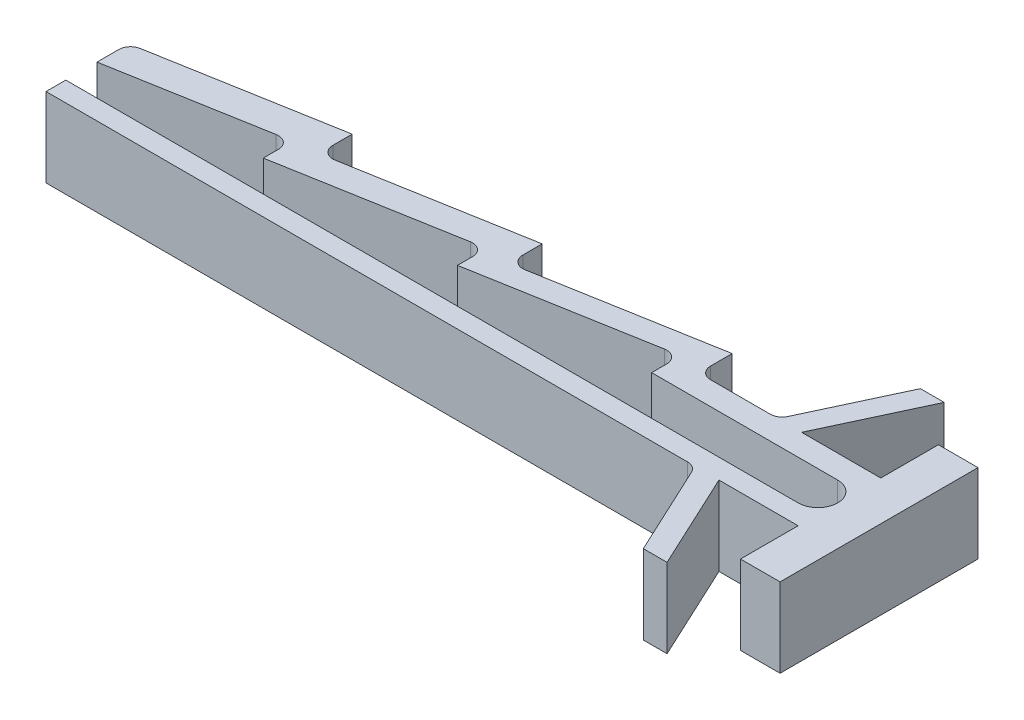
SolidWorks part; units mm, degrees
ref_plane "Front Plane" through (0, 0, 0) normal (0, 0, 1) x (1, 0, 0)
ref_plane "Top Plane" through (0, 0, 0) normal (0, 1, 0) x (1, 0, 0)
ref_plane "Right Plane" through (0, 0, 0) normal (1, 0, 0) x (0, 0, -1)
sketch "Sketch1" plane through (0, 0, 0) normal (0, 1, 0) x (1, 0, 0)
  line L0 (0, 0) -> (0, 0.8)
  line L1 (0, 0.8) -> (4.8, 1.6464)
  line L2 (4.8, 1.6464) -> (4.8, 0.8)
  line L3 (4.8, 0.8) -> (9.6, 1.6464)
  line L4 (9.6, 1.6464) -> (9.6, 0.8)
  line L5 (9.6, 0.8) -> (14.4, 1.6464)
  line L6 (14.4, 1.6464) -> (14.4, 0.8)
  line L7 (14.4, 0.8) -> (16.4, 0.8)
  line L8 (16.4, 0.8) -> (17.5452, 3.2558)
  line L9 (17.5452, 3.2558) -> (18.1452, 3.2558)
  line L10 (18.1452, 3.2558) -> (17, 0.8)
  line L11 (17, 0.8) -> (19, 0.8)
  line L12 (19, 0.8) -> (19, 2.2558)
  line L13 (19, 2.2558) -> (20, 2.2558)
  line L14 (20, 2.2558) -> (20, -2.7442)
  line L15 (20, -2.7442) -> (19, -2.7442)
  line L16 (19, -2.7442) -> (19, -1.2884)
  line L17 (19, -1.2884) -> (17, -1.2884)
  line L18 (0, -1.2884) -> (0, -0.7884)
  line L19 (0, -0.7884) -> (18.5, -0.7884)
  line L21 (18.5, 0.2116) -> (13.8, 0.2116)
  line L22 (16.4, -1.2884) -> (17.5452, -3.7442)
  line L23 (17.5452, -3.7442) -> (18.1452, -3.7442)
  line L24 (18.1452, -3.7442) -> (17, -1.2884)
  line L25 (16.4, -1.2884) -> (0, -1.2884)
  line L26 (0, 0) -> (4.2, 0.7406)
  line L27 (4.2, 0.7406) -> (4.2, 0)
  line L28 (4.2, 0) -> (9, 0.8464)
  line L29 (9, 0.8464) -> (9, 0.1058)
  line L30 (9, 0.1058) -> (13.8, 0.9522)
  line L31 (13.8, 0.9522) -> (13.8, 0.2116)
  arc A0 (18.5, -0.7884) -> (18.5, 0.2116) centre (18.5, -0.2884) ccw
  point P21 (0, 0.4)
  point P34 (0, 0)
  point P36 (3.9166, 0.6906)
  dimension "D1" = 0.6
  dimension "D2" = 0.8
  dimension "D3" = 0.5
  dimension "D4" = 1
  dimension "D5" = 1
  dimension "D6" = 1
  dimension "D7" = 5
  dimension "D8" = 20
  dimension "D9" = 2
  dimension "D10" = 65
  dimension "D11" = 65
  dimension "D12" = 10
  dimension "D13" = 2
  dimension "D14" = 0.6
extrude "Boss-Extrude1" add sketch "Sketch1" along normal blind 2
fillet "Fillet1" radius 0.3 9 edges at (0, 1, -0.8) (13.8, 1, -0.9522) (9, 1, -0.8464) (4.2, 1, -0.7406) (16.4, 1, 1.2884) (16.4, 1, -0.8) (14.4, 1, -0.8) (9.6, 1, -0.8) (4.8, 1, -0.8)
